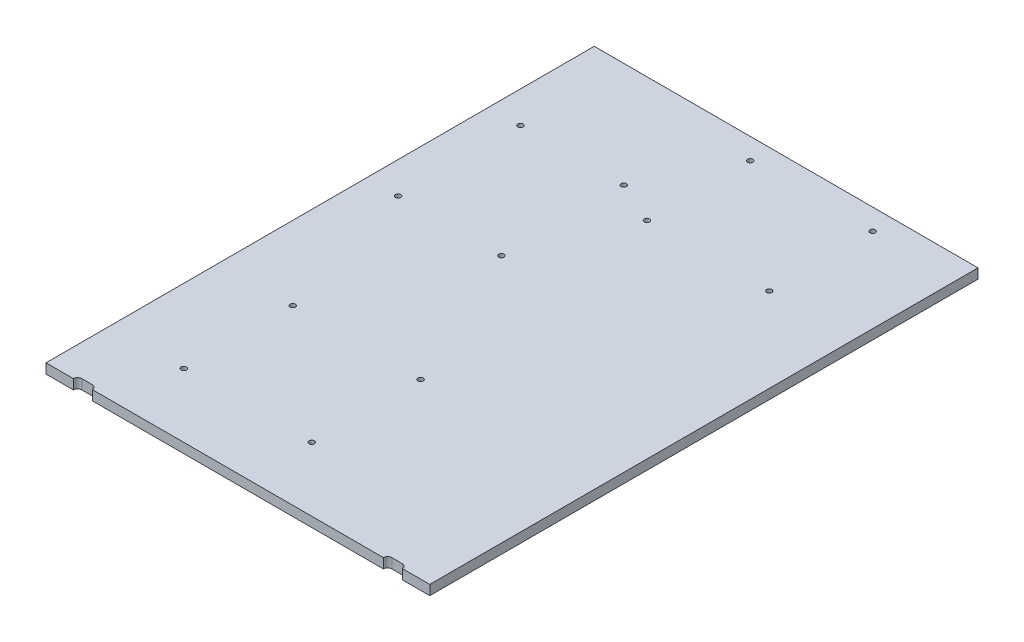
SolidWorks part; units mm, degrees
material "丙烯酸(中高冲击)"
ref_plane "Front" through (0, 0, 0) normal (0, 0, 1) x (1, 0, 0)
ref_plane "Top" through (0, 0, 0) normal (0, 1, 0) x (1, 0, 0)
ref_plane "Right" through (0, 0, 0) normal (1, 0, 0) x (0, 0, -1)
sketch "草图1" plane through (0, 0, 0) normal (0, 1, 0) x (1, 0, 0)
  line L42 (0, 0) -> (182, 0)
  line L43 (0, 0) -> (0, 260)
  line L44 (0, 260) -> (182, 260)
  line L45 (182, 0) -> (182, 260)
  dimension "D1" = 182
  dimension "D2" = 260
extrude "凸台-拉伸1" add sketch "草图1" along normal blind 4.65
fillet "圆角1" [suppressed] radius 1.5
sketch "草图2" plane through (0, 4.65, 0) normal (0, 1, 0) x (1, 0, 0)
  line L0 (15, 2) -> (20, 2)
  line L1 (13, 0) -> (22, 0)
  line L2 (162, 2) -> (167, 2)
  line L3 (160, 0) -> (169, 0)
  line L4 (0, 0) -> (182, 0) construction
  line L5 (0, 260) -> (0, 0) construction
  line L6 (182, 0) -> (182, 260) construction
  arc A0 (15, 2) -> (13, 0) centre (15, 0) ccw
  arc A2 (22, 0) -> (20, 2) centre (20, 0) ccw
  arc A4 (162, 2) -> (160, 0) centre (162, 0) ccw
  arc A5 (169, 0) -> (167, 2) centre (167, 0) ccw
  dimension "D1" = 2
  dimension "D2" = 5
  dimension "D3" = 5
  dimension "D5" = 15
  dimension "D4" = 15
extrude "切除-拉伸1" cut sketch "草图2" against normal up to next
sketch "草图3" plane through (0, 4.65, 0) normal (0, 1, 0) x (1, 0, 0)
  line L0 (182, 260) -> (0, 260) construction
  line L1 (0, 260) -> (0, 0) construction
  circle A0 centre (35, 30.36) radius 1.25
  circle A1 centre (95.65, 30.36) radius 1.25
  circle A2 centre (35, 82) radius 1.25
  circle A3 centre (95.65, 82) radius 1.25
  circle A4 centre (15, 210) radius 1.25
  circle A5 centre (64, 210) radius 1.25
  circle A6 centre (64, 152) radius 1.25
  circle A7 centre (15, 152) radius 1.25
  circle A8 centre (84, 250) radius 1.25
  circle A9 centre (142, 250) radius 1.25
  circle A10 centre (84, 201) radius 1.25
  circle A11 centre (142, 201) radius 1.25
  point P26 (42.5, 16.4128)
  point P27 (42.5, 68.0528)
  point P28 (103.15, 16.4128)
  point P29 (0, 0)
  point P30 (0, 0)
  point P31 (0, 0)
  point P32 (0, 0)
  point P33 (0, 0)
  point P34 (15.0979, 150.7538)
  dimension "D1" = 2.5
  dimension "D7" = 50
  dimension "D2" = 58
  dimension "D3" = 49
  dimension "D4" = 58
  dimension "D5" = 49
  dimension "D6" = 10
  dimension "D8" = 15
  dimension "D9" = 51.64
  dimension "D10" = 60.65
  dimension "D11" = 70
  dimension "D12" = 20
  dimension "D13" = 20
extrude "pcb安装孔" cut sketch "草图3" against normal up to next
